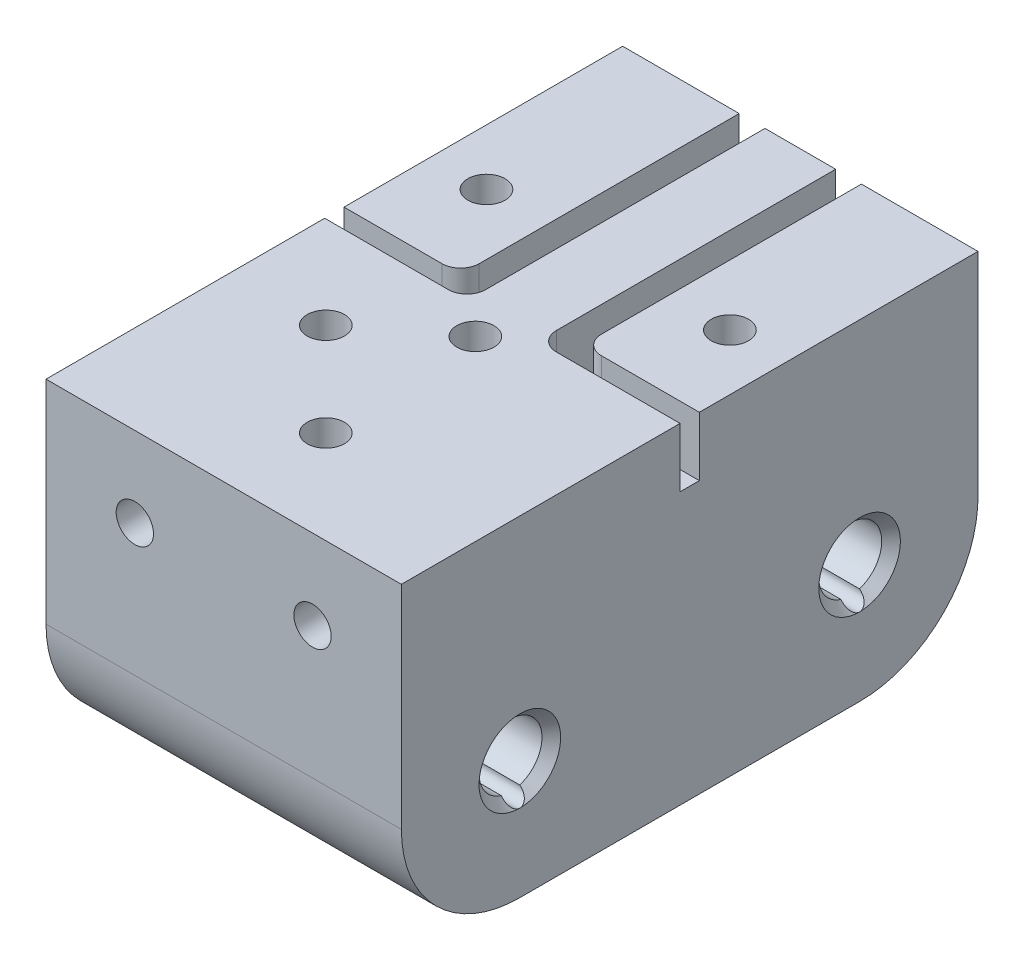
SolidWorks part; units mm, degrees
ref_plane "Front Plane" through (0, 0, 0) normal (0, 0, 1) x (1, 0, 0)
ref_plane "Top Plane" through (0, 0, 0) normal (0, 1, 0) x (1, 0, 0)
ref_plane "Right Plane" through (0, 0, 0) normal (1, 0, 0) x (0, 0, -1)
sketch "Sketch1" plane through (0, 0, 0) normal (1, 0, 0) x (0, 0, -1)
  line L0 (30.9125, 22.75) -> (30.9125, 0) construction
  line L1 (0, 22.75) -> (61.825, 22.75)
  line L2 (0, 22.75) -> (0, 0)
  line L3 (0, 0) -> (61.825, 0)
  line L8 (61.825, 22.75) -> (61.825, 0)
  line L9 (0, 0) -> (0.0025, 0)
  circle A0 centre (12.7025, 0) radius 3.375
  circle A1 centre (49.1275, 0) radius 3.375
  circle A2 centre (12.7025, 0) radius 12.7
  circle A3 centre (49.1275, 0) radius 12.7
  dimension "D2" = 6.75
  dimension "D4" = 25.4
  dimension "D5" = 22.75
  dimension "D3" = 61.825
  dimension "D1" = 12.7025
  dimension "D6" = 49.1275
extrude "Boss-Extrude2" add sketch "Sketch1" along normal blind 38.1
ref_plane "Plane1" through (0, -12.7, 0) normal (0, -1, 0) x (-1, 0, 0)
sketch "Sketch6" plane through (0, -12.7, 0) normal (0, -1, 0) x (-1, 0, 0)
  line L0 (-38.1, 49.1275) -> (0, 49.1275)
  line L1 (-38.1, 61.8275) -> (-38.1, 36.4275) construction
  line L2 (0, 36.4275) -> (0, 61.8275) construction
  line L3 (-38.1, 12.7025) -> (0, 12.7025)
  line L4 (-38.1, 25.4025) -> (-38.1, 0.0025) construction
  line L5 (0, 0.0025) -> (0, 25.4025) construction
  line L7 (-38.1, 49.1275) -> (0, 49.1275)
  line L8 (-38.1, 49.1275) -> (-38.1, 12.7025)
  line L9 (-38.1, 12.7025) -> (0, 12.7025)
  line L10 (0, 49.1275) -> (0, 12.7025)
extrude "Boss-Extrude3" add sketch "Sketch6" against normal up to next
sketch "Sketch10" plane through (0, 0, 0) normal (0, 0, 1) x (1, 0, 0)
  line L0 (38.1, 22.75) -> (38.1, 0) construction
  line L1 (0, 22.75) -> (38.1, 22.75)
  line L2 (0, 22.75) -> (0, 5.5563)
  line L3 (0, 5.5563) -> (38.1, 5.5563)
  line L4 (38.1, 22.75) -> (38.1, 5.5563)
  line L5 (19.05, 22.75) -> (19.05, 5.5563) construction
  line L6 (0, 14.1531) -> (19.05, 14.1531) construction
  line L7 (19.05, 14.1531) -> (38.1, 14.1531) construction
  circle A0 centre (9.525, 14.1531) radius 2
  circle A1 centre (28.575, 14.1531) radius 2
  dimension "D2" = 4
  dimension "D1" = 17.1937
extrude "Cut-Extrude6" cut sketch "Sketch10" against normal blind 8 contours A0 | A1
chamfer "Chamfer1" distance 1 angle 45 4 edges at (38.1, 0, -16.0775) (0, 0, -16.0775) (38.1, 0, -52.5025) (0, 0, -52.5025)
sketch "Sketch15" plane through (0, 22.75, 0) normal (0, 1, 0) x (1, 0, 0)
  line L0 (0, 61.825) -> (38.1, 61.825) construction
  line L5 (0, 31.95) -> (12.5, 31.95)
  line L6 (12.5, 31.95) -> (12.5, 61.825)
  line L8 (15.26, 61.825) -> (15.26, 29.88)
  line L9 (15.26, 29.88) -> (0, 29.88)
  line L12 (19.05, 19.555) -> (19.05, 61.825) construction
  line L13 (0, 30.9125) -> (38.1, 30.9125) construction
  line L14 (22.84, 29.88) -> (38.1, 29.88)
  line L15 (22.84, 61.825) -> (22.84, 29.88)
  line L17 (25.6, 31.95) -> (25.6, 61.825)
  line L18 (38.1, 31.95) -> (25.6, 31.95)
  line L20 (0, 61.825) -> (38.1, 61.825)
  line L21 (0, 61.825) -> (0, 19.555)
  line L22 (0, 19.555) -> (38.1, 19.555)
  line L23 (38.1, 61.825) -> (38.1, 19.555)
  line L24 (0, 0) -> (0, 61.825) construction
  line L25 (0, 29.88) -> (0, 19.555) construction
  line L26 (38.1, 0) -> (38.1, 61.825) construction
  line L27 (38.1, 61.825) -> (0, 61.825) construction
  line M70 (0, 61.825) -> (0, 0)
  line M72 (38.1, 0) -> (38.1, 61.825)
  line M82 (38.1, 61.825) -> (0, 61.825)
  dimension "D2" = 10.325
  dimension "D4" = 12.395
  dimension "D5" = 12.5
  dimension "D6" = 15.26
  dimension "D1" = 1.0375
sketch "Sketch16" plane through (0, 22.75, 0) normal (0, 1, 0) x (1, 0, 0)
  line L0 (19.05, 61.825) -> (19.05, 21.825) construction
  line L1 (0, 61.825) -> (38.1, 61.825)
  line L2 (0, 61.825) -> (0, 21.825)
  line L3 (0, 21.825) -> (38.1, 21.825)
  line L4 (38.1, 61.825) -> (38.1, 21.825)
  line L6 (0, 0) -> (20, 0)
  line L7 (0, 0) -> (0, 20)
  line L8 (0, 20) -> (20, 20)
  line L9 (20, 0) -> (20, 20)
  circle A0 centre (19.05, 26.985) radius 2
  circle A1 centre (6, 41.225) radius 2
  circle A2 centre (32.1, 41.225) radius 2
  circle A3 centre (20, 10) radius 2
  circle A4 centre (10, 20) radius 2
  dimension "D6" = 4
  dimension "D9" = 4
  dimension "D10" = 4
  dimension "D1" = 19.4
  dimension "D2" = 38.1
  dimension "D3" = 5.16
  dimension "D4" = 40
  dimension "D5" = 6
  dimension "D7" = 20
  dimension "D8" = 20
extrude "Cut-Extrude11" cut sketch "Sketch15" against normal blind 6.35 contours L9 L8 L6 L5 M82 M70 | L18 L17 L15 L14 M72 M82
extrude "Cut-Extrude10" cut sketch "Sketch16" against normal blind 5 contours A2 | L0 A0 | A0 L0 | A1 | A4 | A3
sketch "Sketch17" plane through (38.1, 0, 0) normal (1, 0, 0) x (0, 0, -1)
  circle A0 centre (12.7025, -3.375) radius 1
  circle A1 centre (12.7025, 0) radius 3.375 construction
  circle A2 centre (49.1275, -3.375) radius 1
  circle A3 centre (49.1275, 0) radius 3.375 construction
  dimension "D1" = 2
  dimension "D2" = 2
extrude "Cut-Extrude12" cut sketch "Sketch17" against normal through all
fillet "Fillet1" radius 2 4 edges at (12.5, 19.575, -31.95) (15.26, 19.575, -29.88) (25.6, 19.575, -31.95) (22.84, 19.575, -29.88)
equation "\"Ø Smaller Shaft\"=6.35"
equation "\"Shaft Distance\"= 36.425"
equation "\"Width\"= \"Ø Smaller Shaft\" * 2 + \"Shaft Distance\" + \"Width End\" * 2"
equation "\"Width End\"= 6.35"
equation "\"Length\"= 38.1"
equation "\"Rod to Belt\"= 31.75 + 3"
equation "\"Nom Tolerance\"= 0.15"
equation "\"Belt\"= 6"
equation "\"Belt Thickness\"=1.38"
equation "\"Ø Pulley\"= 10.9"
equation "\"Pully Distance\"= 35"
equation "\"D5@Sketch1\"=\"Rod to Belt\"+(\"Belt\"/2)-15"
equation "\"D1@Boss-Extrude2\"=\"Length\""
equation "\"Ø Outer Washer\"=12.7"
equation "\"Washer Thickness\"=2"
equation "\"D1\"= \"Washer Thickness\""
equation "\"M3 Heated Insert Hole\"= 4"
equation "\"D1@Sketch10\"=\"Rod to Belt\"+(\"Belt\"/2)-15-(\"Ø Smaller Shaft\"*1.75)/2"
equation "\"D2@Sketch10\"=\"M3 Heated Insert Hole\""
equation "\"Ø Graphite Holder\"= 17"
equation "\"D3@Sketch1\"=50.80 + (5.5125*2)"
equation "\"D1@Sketch15\"=(12.4-10.325)/2"
